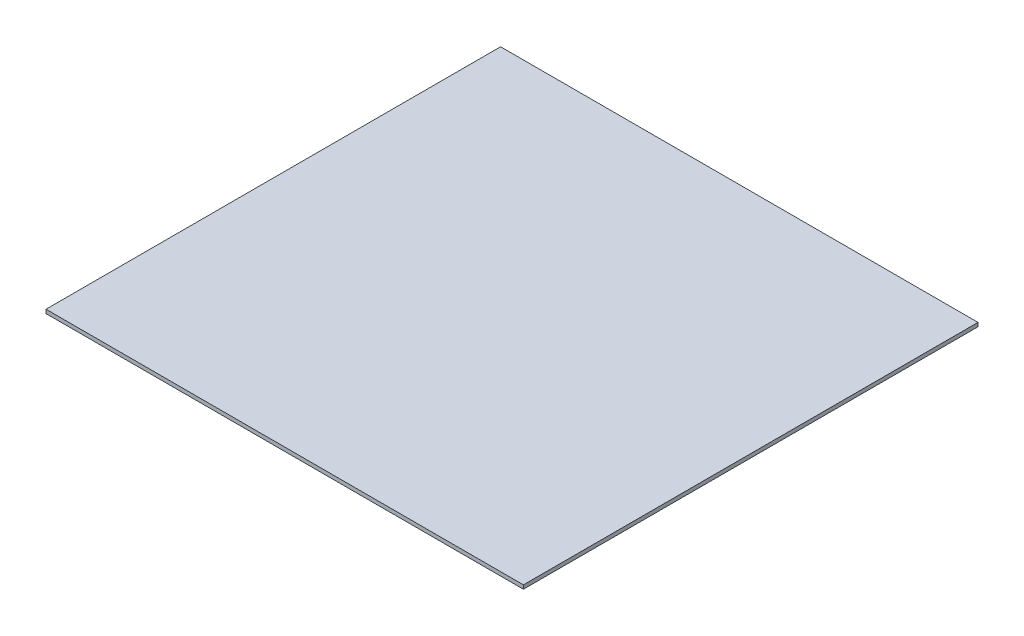
SolidWorks part; units mm, degrees
ref_plane "Front Plane" through (0, 0, 0) normal (0, 0, 1) x (1, 0, 0)
ref_plane "Top Plane" through (0, 0, 0) normal (0, 1, 0) x (1, 0, 0)
ref_plane "Right Plane" through (0, 0, 0) normal (1, 0, 0) x (0, 0, -1)
sketch "Sketch1" plane through (0, 0, 0) normal (0, 1, 0) x (1, 0, 0)
  line L1 (-93.0918, 179.6824) -> (157.9082, 179.6824)
  line L2 (-93.0918, 179.6824) -> (-93.0918, -59.3176)
  line L3 (-93.0918, -59.3176) -> (157.9082, -59.3176)
  line L4 (157.9082, 179.6824) -> (157.9082, -59.3176)
  dimension "D1" = 251
  dimension "D2" = 239
extrude "Boss-Extrude1" add sketch "Sketch1" along normal blind 2
